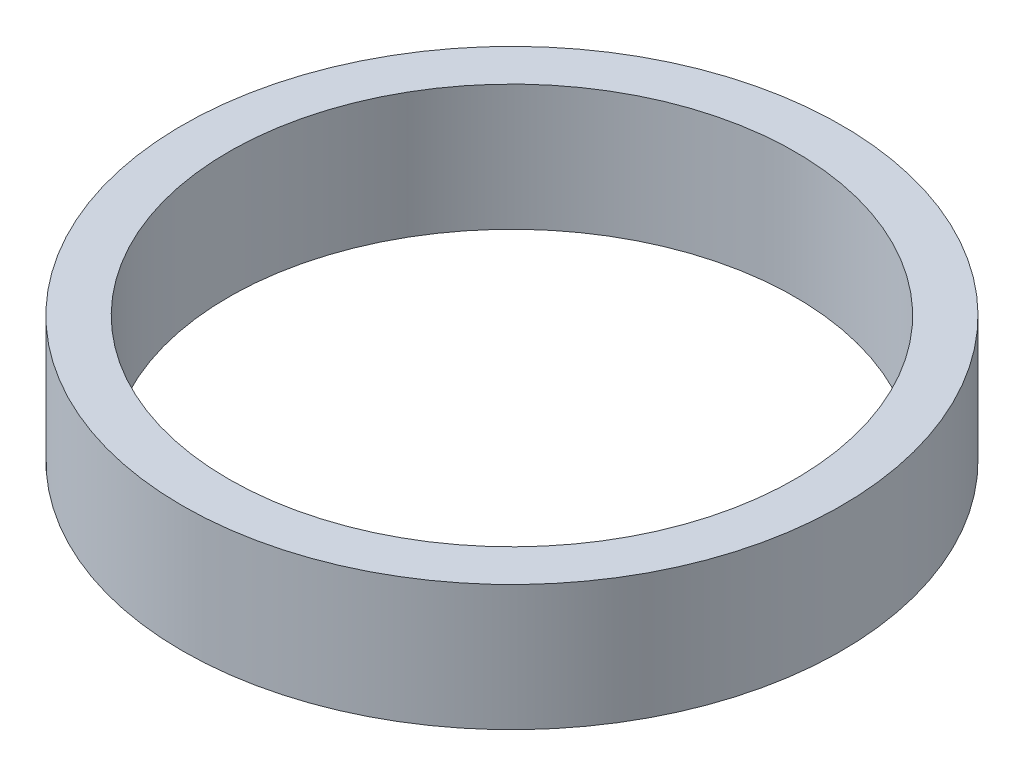
SolidWorks part; units mm, degrees
ref_plane "前视基准面" through (0, 0, 0) normal (0, 0, 1) x (1, 0, 0)
ref_plane "上视基准面" through (0, 0, 0) normal (0, 1, 0) x (1, 0, 0)
ref_plane "右视基准面" through (0, 0, 0) normal (1, 0, 0) x (0, 0, -1)
sketch "草图1" plane through (0, 0, 0) normal (0, 1, 0) x (1, 0, 0)
  circle A0 centre (0, 0) radius 9.015
  circle A1 centre (0, 0) radius 10.485
  dimension "D1" = 20.97
  dimension "D2" = 18.03
extrude "凸台-拉伸1" add sketch "草图1" along normal blind 4
